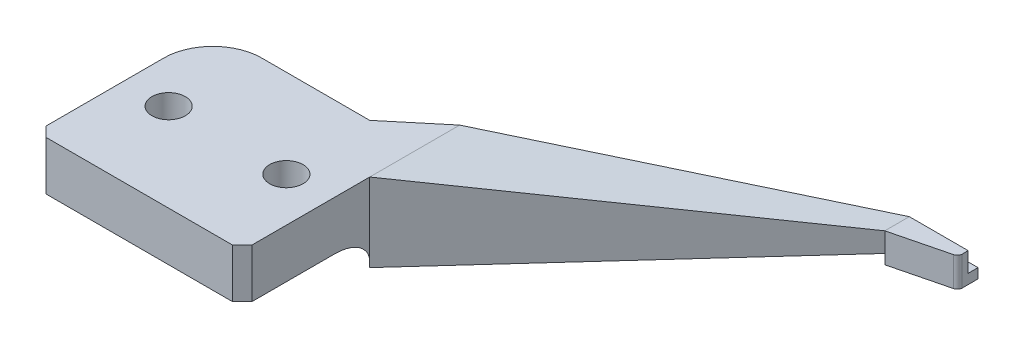
SolidWorks part; units mm, degrees
ref_plane "正面" through (0, 0, 0) normal (0, 0, 1) x (1, 0, 0)
ref_plane "平面" through (0, 0, 0) normal (0, 1, 0) x (1, 0, 0)
ref_plane "右側面" through (0, 0, 0) normal (1, 0, 0) x (0, 0, -1)
sketch "ｽｹｯﾁ2" plane through (0, 0, 0) normal (0, 1, 0) x (1, 0, 0)
  line L1 (-10.5, -9) -> (10.5, -9)
  line L2 (-10.5, -9) -> (-10.5, 9)
  line L3 (-10.5, 9) -> (10.5, 9)
  line L4 (10.5, -9) -> (10.5, 9)
  line L5 (-10.5, -9) -> (10.5, 9) construction
  line L6 (-10.5, 9) -> (10.5, -9) construction
  point P0 (0, 0)
  dimension "D1" = 21
  dimension "D2" = 18
extrude "ﾎﾞｽ - 押し出し2" add sketch "ｽｹｯﾁ2" along normal blind 5
ref_plane "平面1" through (0, -4, 0) normal (0, -1, 0) x (-1, 0, 0)
sketch "ｽｹｯﾁ3" plane through (0, -4, 0) normal (0, -1, 0) x (-1, 0, 0)
  line L0 (-5.5, 9) -> (-35.5, 34)
  line L1 (-10.5, 9) -> (10.5, 9) construction
  line L2 (-35.5, 34) -> (-41.5, 34)
  line L3 (-41.5, 34) -> (-41.5, 33)
  line L4 (-10.5, 4) -> (-35.5, 31.5)
  line L6 (-10.5, -9) -> (-10.5, 9) construction
  line L7 (-35.5, 31.5) -> (-41.5, 33)
  line L8 (-10.5, 4) -> (-5.5, 9)
  dimension "D1" = 25
  dimension "D2" = 5
  dimension "D3" = 5
  dimension "D4" = 6
  dimension "D5" = 1
  dimension "D6" = 25
  dimension "D7" = 2.5
extrude "ﾎﾞｽ - 押し出し3" add sketch "ｽｹｯﾁ3" against normal blind 9
sketch "ｽｹｯﾁ4" plane through (0, 0, 9) normal (0, 0, 1) x (1, 0, 0)
  line L0 (35.5, -1) -> (10.5, 5)
  line L1 (35.5, 5) -> (35.5, -4) construction
  line L2 (10.5, 5) -> (41.5, 5)
  line L3 (41.5, 5) -> (41.5, -1)
  line L4 (41.5, 5) -> (41.5, -4) construction
  line L5 (35.5, -1) -> (41.5, -1)
  line L6 (-18.5688, -4) -> (18.5688, -4) construction
  line L7 (5.5, -4) -> (35.5, -4)
  line L8 (35.5, -4) -> (35.5, -3)
  line L9 (35.5, -3) -> (5.5, -3)
  line L10 (5.5, 0) -> (5.5, -4) construction
  line L11 (5.5, -3) -> (5.5, -4)
  dimension "D1" = 3
  dimension "D2" = 1
extrude "ｶｯﾄ - 押し出し1" cut sketch "ｽｹｯﾁ4" against normal through all
fillet "ﾌｨﾚｯﾄ1" radius 0.5 1 edges at (41.5, -2.5, -33)
fillet "ﾌｨﾚｯﾄ2" radius 2.5 1 edges at (8, 0, -6.5)
fillet "ﾌｨﾚｯﾄ3" radius 5 1 edges at (-10.5, 2.5, -9)
chamfer "面取り1" distance 1 angle 45 2 edges at (-10.5, 2.5, 9) (10.5, 2.5, 9)
sketch "ｽｹｯﾁ5" plane through (0, 5, 0) normal (0, 1, 0) x (1, 0, 0)
  line L0 (-9.5, -9) -> (9.5, -9) construction
  line L1 (0, 0) -> (0, -1.8564) construction
  circle A0 centre (6, 0) radius 1.7
  circle A1 centre (-6, 0) radius 1.7
  dimension "D4" = 3.4
  dimension "D1" = 9
  dimension "D2" = 6
  dimension "D3" = 6
extrude "ｶｯﾄ - 押し出し2" cut sketch "ｽｹｯﾁ5" against normal through all
sketch "ｽｹｯﾁ6" plane through (0, 0, -34) normal (0, 0, -1) x (-1, 0, 0)
  line L0 (-35.5, -4) -> (-41.5, -4) construction
  line L1 (-35.5, -3) -> (-41.5, -3)
  line L2 (-35.5, -3) -> (-35.5, -4)
  line L3 (-35.5, -4) -> (-41.5, -4)
  line L4 (-41.5, -3) -> (-41.5, -4)
  line L5 (-35.5, -3) -> (-41.5, -4) construction
  line L6 (-35.5, -4) -> (-41.5, -3) construction
  line L7 (-35.5, -4) -> (-35.5, -3) construction
  point P0 (-38.5, -3.5)
  point P7 (-35.5, -4)
  point P10 (-41.5, -4)
  dimension "D1" = 1
extrude "ﾎﾞｽ - 押し出し4" add sketch "ｽｹｯﾁ6" along normal blind 1
